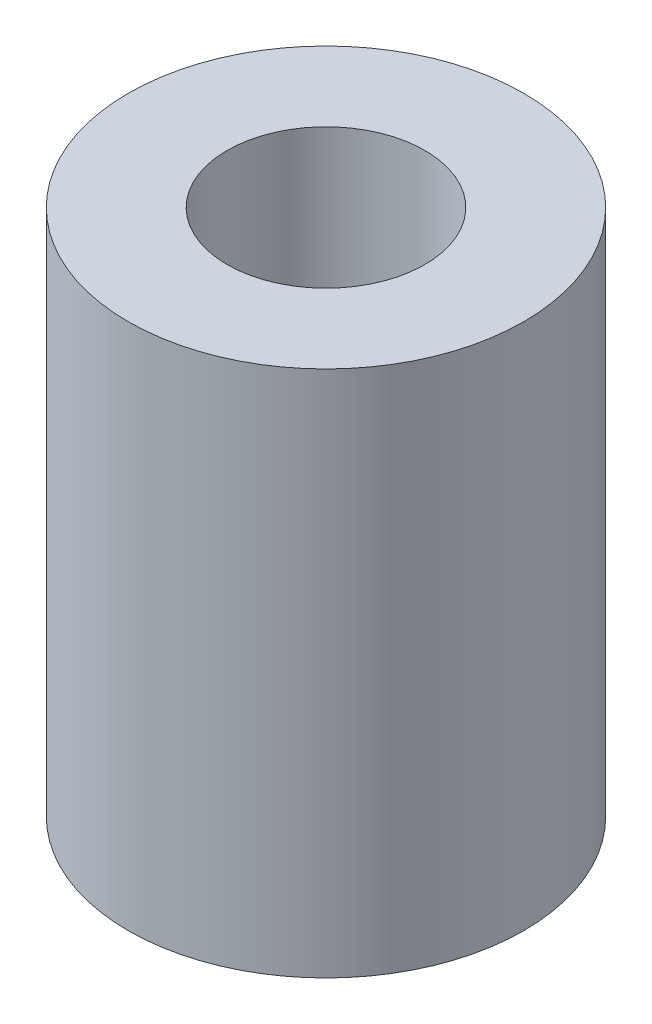
SolidWorks part; units mm, degrees
ref_plane "Front" through (0, 0, 0) normal (0, 0, 1) x (1, 0, 0)
ref_plane "Top" through (0, 0, 0) normal (0, 1, 0) x (1, 0, 0)
ref_plane "Right" through (0, 0, 0) normal (1, 0, 0) x (0, 0, -1)
sketch "Sketch1" plane through (0, 0, 0) normal (0, 1, 0) x (1, 0, 0)
  circle A0 centre (0, 0) radius 3
  circle A1 centre (0, 0) radius 1.5
  dimension "D1" = 3
  dimension "D2" = 6
extrude "Boss-Extrude1" add sketch "Sketch1" along normal blind 8
